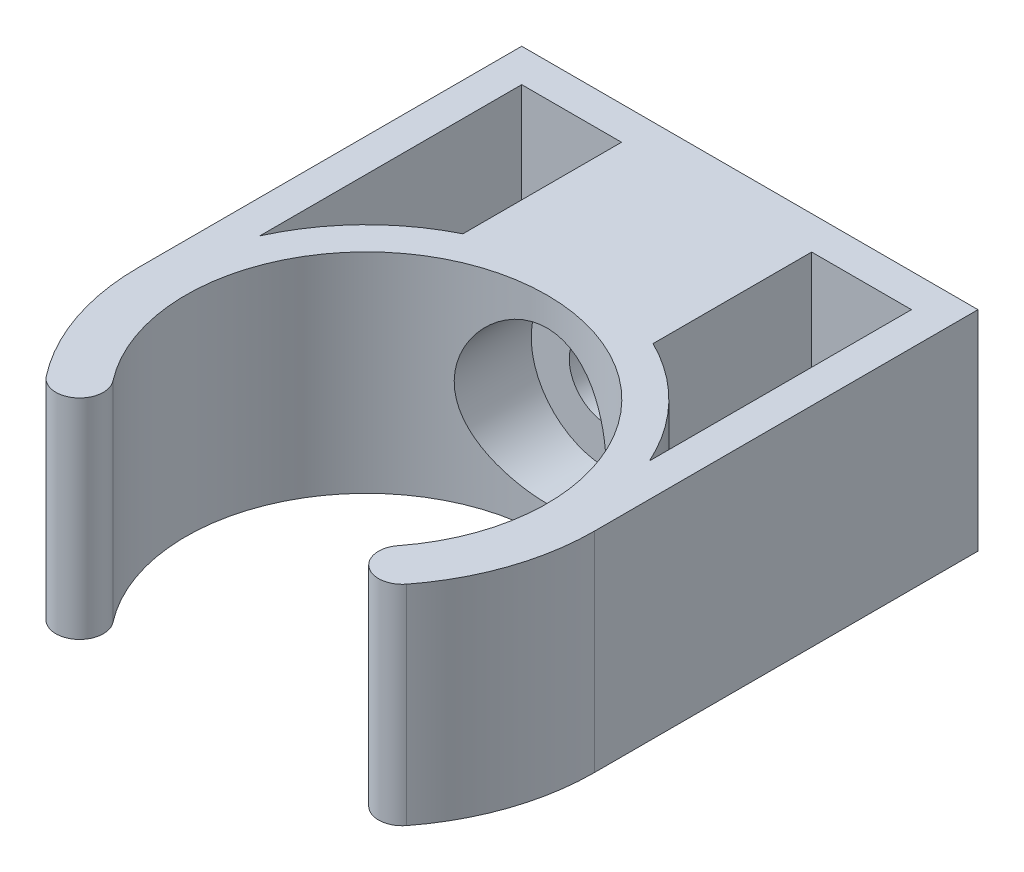
SolidWorks part; units mm, degrees
material "ABS"
ref_plane "Front Plane" through (0, 0, 0) normal (0, 0, 1) x (1, 0, 0)
ref_plane "Top Plane" through (0, 0, 0) normal (0, 1, 0) x (1, 0, 0)
ref_plane "Right Plane" through (0, 0, 0) normal (1, 0, 0) x (0, 0, -1)
sketch "Sketch1" plane through (0, 0, 0) normal (0, 1, 0) x (1, 0, 0)
  line L2 (-12, -7.169) -> (-12, 13)
  line L3 (-12, 13) -> (12, 13)
  line L4 (12, -7.169) -> (12, 13)
  arc A0 (7.5, -13) -> (-7.5, -13) centre (0, -7.169) ccw
  arc A1 (9.4737, -14.5345) -> (12, -7.169) centre (0, -7.169) ccw
  arc A2 (-7.5, -13) -> (-9.4737, -14.5345) centre (-8.4868, -13.7672) cw
  arc A3 (7.5, -13) -> (9.4737, -14.5345) centre (8.4868, -13.7672) ccw
  arc A4 (-12, -7.169) -> (-9.4737, -14.5345) centre (0, -7.169) ccw
  point P0 (0, 0)
  point P8 (-7.5, -13)
  point P10 (7.5, -13)
  dimension "D3" = 15
  dimension "D4" = 13
  dimension "D2" = 9.5
  dimension "D1" = 24
  dimension "D5" = 7.169
extrude "Boss-Extrude1" add sketch "Sketch1" along normal blind 11
shell "Shell2" thickness 1.75
sketch "Sketch5" plane through (0, 11, 0) normal (0, 1, 0) x (1, 0, 0)
  line L0 (12, 13) -> (-12, 13) construction
  line L1 (-5, 2.331) -> (5, 2.331)
  line L2 (-5, 2.331) -> (-5, 13)
  line L3 (-5, 13) -> (5, 13)
  line L4 (5, 2.331) -> (5, 13)
  line L5 (-5, 2.331) -> (5, 13) construction
  line L6 (-5, 13) -> (5, 2.331) construction
  arc A0 (7.5, -13) -> (-7.5, -13) centre (0, -7.169) ccw construction
  point P0 (0, 7.6655)
  point P7 (0, 0)
  dimension "D1" = 10
extrude "Boss-Extrude2" add sketch "Sketch5" against normal up to surface (9.25 mm away) up to face at (0, 1.75, -6.0122)
hole_wizard "Hole4" positions "Sketch2" profile "Sketch4" legacy end condition through all
sketch "Sketch2" plane through (0, 0, 0) normal (0, 0, 1) x (1, 0, 0)
  line L9 (-9.5, 0) -> (9.5, 0) construction
  point P0 (0, 5.5)
  dimension "D1" = 5.5
sketch "Sketch4" plane through (0, 5.5, 0) normal (1, 0, 0) x (0, -1, 0)
  line L0 (0, 0) -> (0, 14.2017)
  line L1 (0, 14.2017) -> (2, 13)
  line L2 (2, 13) -> (2, 5.5)
  line L3 (2, 5.5) -> (4, 5.5)
  line L4 (4, 0) -> (0, 0)
  line L5 (0, -11.3109) -> (0, 121.1557) construction
  line L6 (0, 14.2017) -> (-2, 13) construction
  line L7 (4, 5.5) -> (4, 0)
  dimension "Depth" = 13
  dimension "Drill Angle" = 118
  dimension "Diameter" = 4
  dimension "C-Bore Diameter" = 8
  dimension "C-Bore Depth" = 5.5
